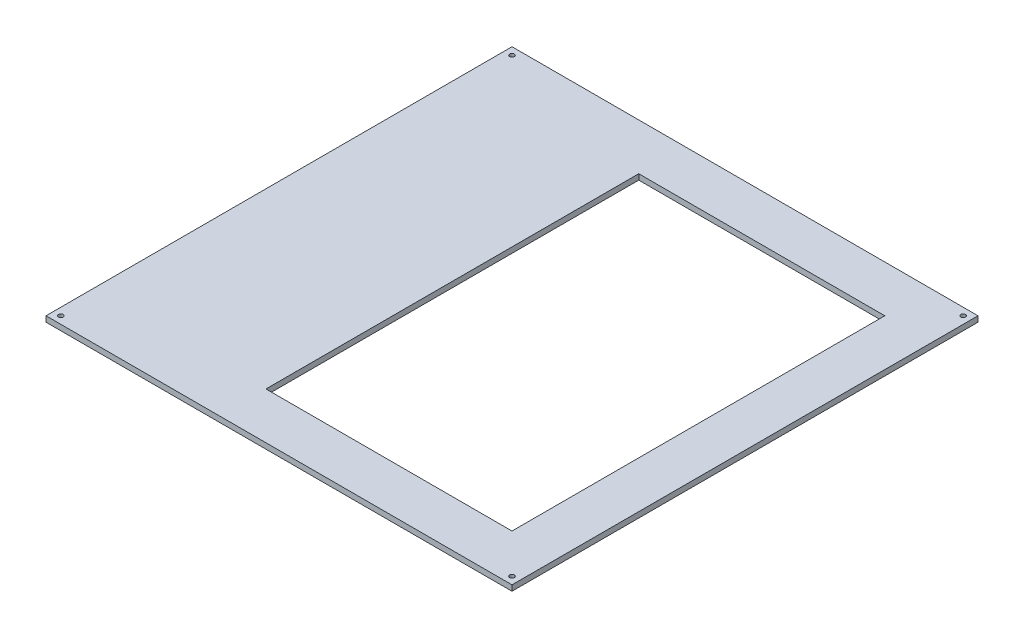
SolidWorks part; units mm, degrees
ref_plane "Спереди" through (0, 0, 0) normal (0, 0, 1) x (1, 0, 0)
ref_plane "Сверху" through (0, 0, 0) normal (0, 1, 0) x (1, 0, 0)
ref_plane "Справа" through (0, 0, 0) normal (1, 0, 0) x (0, 0, -1)
sketch "Эскиз1" plane through (0, 0, 0) normal (0, 1, 0) x (1, 0, 0)
  line L1 (-125, -125) -> (125, -125)
  line L2 (-125, -125) -> (-125, 125)
  line L3 (-125, 125) -> (125, 125)
  line L4 (125, -125) -> (125, 125)
  line L5 (-125, -125) -> (125, 125) construction
  line L6 (-125, 125) -> (125, -125) construction
  point P0 (0, 0)
  dimension "D1" = 250
  dimension "D2" = 250
extrude "Бобышка-Вытянуть1" add sketch "Эскиз1" along normal blind 3
sketch "Эскиз3" plane through (0, 0, 0) normal (0, -1, 0) x (1, 0, 0)
  line L0 (-125, -125) -> (-125, 125) construction
  line L1 (-32, 100) -> (100, 100)
  line L2 (-32, 100) -> (-32, -100)
  line L3 (-32, -100) -> (100, -100)
  line L4 (100, 100) -> (100, -100)
  line L5 (-32, 100) -> (100, -100) construction
  line L6 (-32, -100) -> (100, 100) construction
  line L7 (125, -125) -> (-125, -125) construction
  line L8 (-125, 125) -> (125, 125) construction
  line L9 (125, 125) -> (125, -125) construction
  point P0 (34, 0)
  dimension "D1" = 93
  dimension "D2" = 25
  dimension "D3" = 25
  dimension "D4" = 25
extrude "Вырез-Вытянуть1" cut sketch "Эскиз3" against normal blind 10
sketch "Эскиз4" plane through (0, 0, 0) normal (0, -1, 0) x (1, 0, 0)
  line L0 (-125, 125) -> (125, 125) construction
  line L1 (-125, -125) -> (-125, 125) construction
  line L2 (125, 125) -> (125, -125) construction
  line L3 (125, -125) -> (-125, -125) construction
  circle A0 centre (-121, 121) radius 1.25
  circle A1 centre (121, 121) radius 1.25
  circle A2 centre (121, -121) radius 1.25
  circle A3 centre (-121, -121) radius 1.25
  dimension "D1" = 2.5
  dimension "D4" = 2.5
  dimension "D7" = 2.5
  dimension "D11" = 2.5
  dimension "D2" = 4
  dimension "D3" = 4
  dimension "D5" = 4
  dimension "D6" = 4
  dimension "D8" = 4
  dimension "D9" = 4
  dimension "D10" = 4
  dimension "D12" = 4
extrude "Вырез-Вытянуть2" cut sketch "Эскиз4" against normal blind 10
